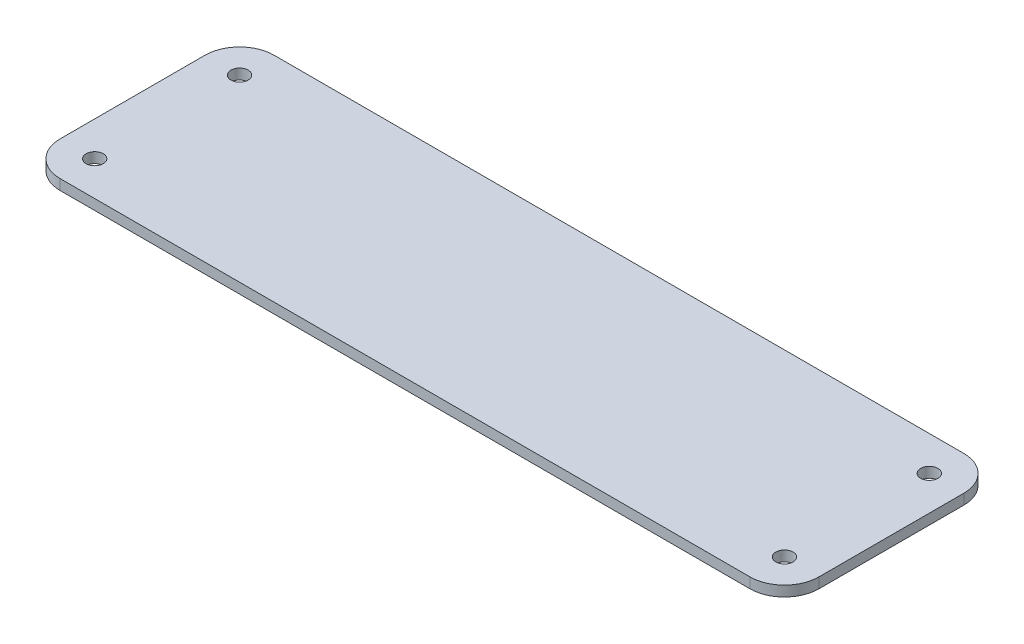
SolidWorks part; units mm, degrees
ref_plane "Front Plane" through (0, 0, 0) normal (0, 0, 1) x (1, 0, 0)
ref_plane "Top Plane" through (0, 0, 0) normal (0, 1, 0) x (1, 0, 0)
ref_plane "Right Plane" through (0, 0, 0) normal (1, 0, 0) x (0, 0, -1)
sketch "Sketch1" plane through (0, 0, 0) normal (0, 1, 0) x (1, 0, 0)
  line L0 (0, 0) -> (0, 62) construction
  line L1 (-100, 62) -> (100, 62)
  line L2 (-110, 52) -> (-110, 10)
  line L3 (-100, 0) -> (100, 0)
  line L4 (110, 52) -> (110, 10)
  circle A0 centre (-100, 52) radius 2.5
  circle A1 centre (-100, 10) radius 2.5
  circle A2 centre (100, 52) radius 2.5
  circle A3 centre (100, 10) radius 2.5
  arc A4 (-110, 10) -> (-100, 0) centre (-100, 10) ccw
  arc A5 (100, 0) -> (110, 10) centre (100, 10) ccw
  arc A6 (100, 62) -> (110, 52) centre (100, 52) cw
  arc A7 (-100, 62) -> (-110, 52) centre (-100, 52) ccw
  point P15 (0, 0)
  point P16 (-110, -17.4745)
  point P17 (-110, 55.1825)
  point P18 (110, -11.4352)
  point P19 (0, 0)
  point P20 (-110, 4.8269)
  point P21 (0, 0)
  point P26 (110, 0)
  point P29 (110, 62)
  point P32 (-110, 62)
  dimension "D1" = 42
  dimension "D2" = 5
  dimension "D4" = 200
  dimension "D6" = 10
  dimension "D7" = 10
  dimension "D3" = 220
  dimension "D5" = 10
extrude "Boss-Extrude1" add sketch "Sketch1" along normal blind 3
